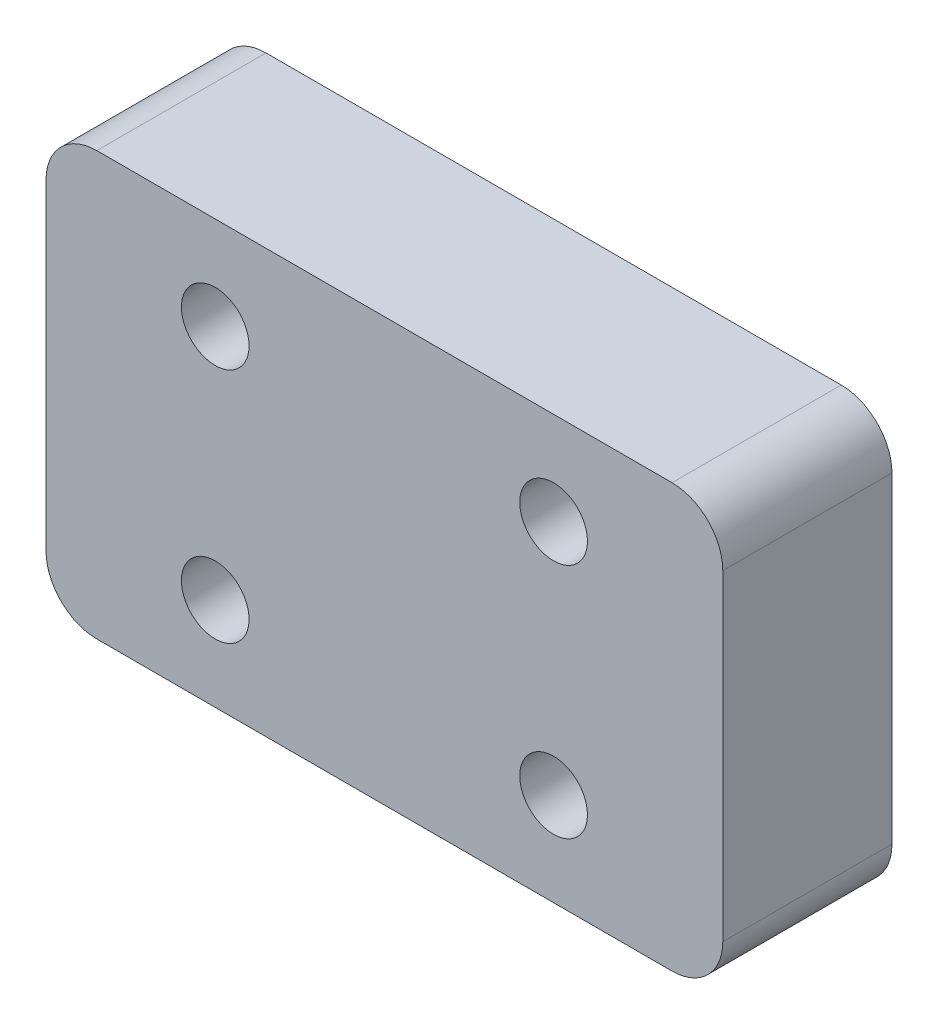
SolidWorks part; units mm, degrees
ref_plane "前视基准面" through (0, 0, 0) normal (0, 0, 1) x (1, 0, 0)
ref_plane "上视基准面" through (0, 0, 0) normal (0, 1, 0) x (1, 0, 0)
ref_plane "右视基准面" through (0, 0, 0) normal (1, 0, 0) x (0, 0, -1)
other "Configuration Table"
sketch "草图1" plane through (0, 0, 0) normal (0, 0, 1) x (1, 0, 0)
  line L1 (-3, 0) -> (-37, 0)
  line L2 (0, 3) -> (0, 22)
  line L3 (-3, 25) -> (-37, 25)
  line L4 (-40, 3) -> (-40, 22)
  arc A0 (-3, 25) -> (0, 22) centre (-3, 22) cw
  arc A1 (-3, 0) -> (0, 3) centre (-3, 3) ccw
  arc A2 (-37, 0) -> (-40, 3) centre (-37, 3) cw
  arc A3 (-40, 22) -> (-37, 25) centre (-37, 22) cw
  point P7 (0, 25)
  point P10 (0, 0)
  point P13 (-40, 0)
  dimension "D3" = 3
  dimension "D1" = 25
  dimension "D2" = 40
extrude "凸台-拉伸1" add sketch "草图1" along normal blind 10
sketch "草图3" plane through (0, 0, 10) normal (0, 0, 1) x (1, 0, 0)
  line L0 (-40, 12.5) -> (0, 12.5) construction
  line L1 (-40, 22) -> (-40, 3) construction
  line L2 (0, 3) -> (0, 22) construction
  line L3 (-20, 0) -> (-20, 25) construction
  line L4 (-37, 0) -> (-3, 0) construction
  line L5 (-3, 25) -> (-37, 25) construction
  circle A0 centre (-30, 19.5) radius 2
  circle A1 centre (-30, 5.5) radius 2
  circle A2 centre (-10, 19.5) radius 2
  circle A3 centre (-10, 5.5) radius 2
  dimension "D1" = 4
  dimension "D2" = 20
  dimension "D3" = 14
extrude "切除-拉伸1" cut sketch "草图3" against normal up to next
